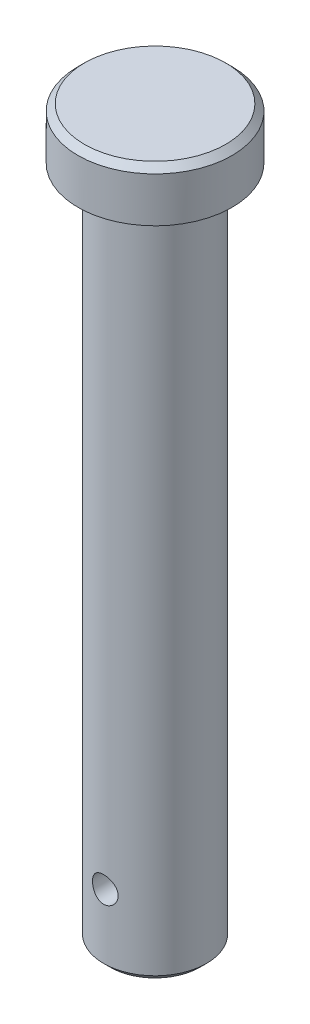
SolidWorks part; units mm, degrees
ref_plane "Front Plane" through (0, 0, 0) normal (0, 0, 1) x (1, 0, 0)
ref_plane "Top Plane" through (0, 0, 0) normal (0, 1, 0) x (1, 0, 0)
ref_plane "Right Plane" through (0, 0, 0) normal (1, 0, 0) x (0, 0, -1)
sketch "Sketch1" plane through (0, 0, 0) normal (0, 0, 1) x (1, 0, 0)
  line L0 (0, -56.5) -> (0, 56.5)
  line L1 (0, 56.5) -> (12, 56.5)
  line L2 (12, 56.5) -> (12, 48.5)
  line L3 (12, 48.5) -> (8, 48.5)
  line L4 (8, 48.5) -> (8, -56.5)
  line L5 (8, -56.5) -> (0, -56.5)
  point P4 (0, 0)
  dimension "D1" = 113
  dimension "D2" = 12
  dimension "D3" = 8
  dimension "D4" = 4
revolve "Revolve1" add sketch "Sketch1" angle 360 about L0
chamfer "Chamfer1" distance 1 angle 45 1 edges at (0, 56.5, -12)
chamfer "Chamfer2" distance 1 angle 45 1 edges at (0, -56.5, -8)
sketch "Sketch2" plane through (0, 0, 0) normal (0, 0, 1) x (1, 0, 0)
  line L0 (0, 48.5) -> (0, -45.5)
  line L1 (-8, 48.5) -> (8, 48.5) construction
  circle A0 centre (0, -45.5) radius 2
  dimension "D2" = 4
  dimension "D1" = 94
extrude "Cut-Extrude2" cut sketch "Sketch2" against normal mid plane 50
